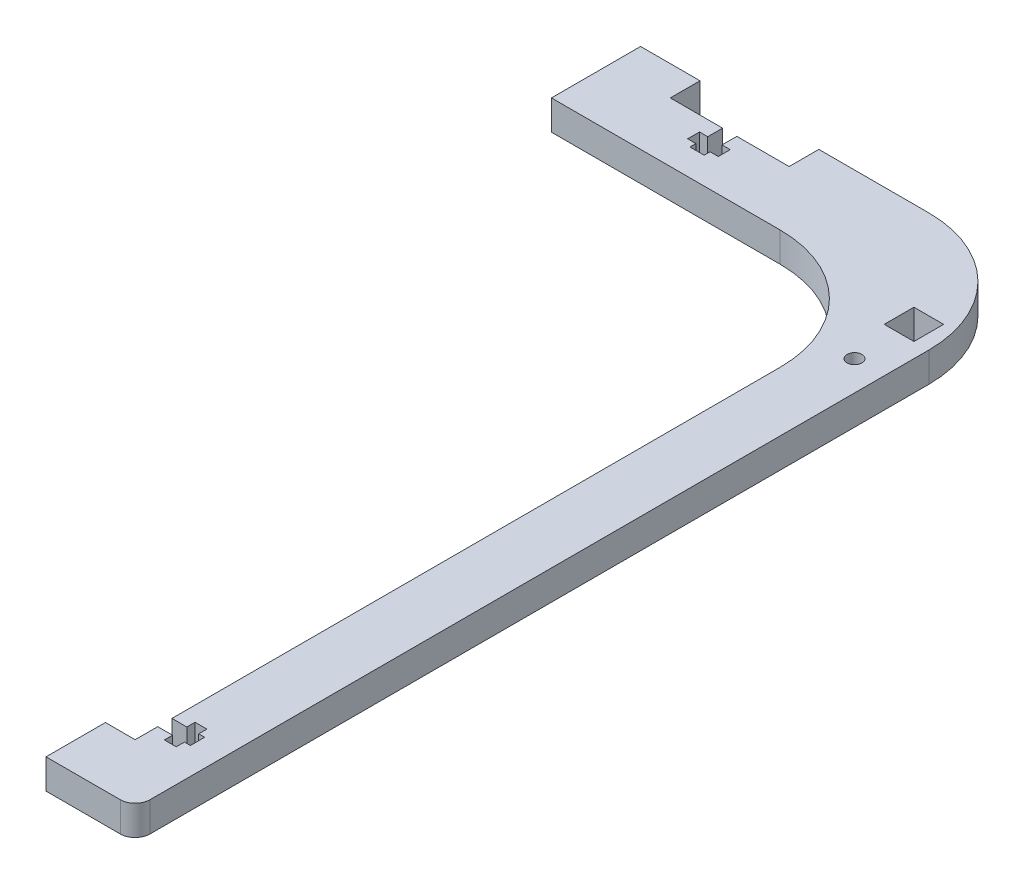
SolidWorks part; units mm, degrees
material "6061 Alloy"
ref_plane "Front Plane" through (0, 0, 0) normal (0, 0, 1) x (1, 0, 0)
ref_plane "Top Plane" through (0, 0, 0) normal (0, 1, 0) x (1, 0, 0)
ref_plane "Right Plane" through (0, 0, 0) normal (1, 0, 0) x (0, 0, -1)
sketch "Sketch1" plane through (0, 0, 0) normal (0, 1, 0) x (1, 0, 0)
  line L0 (7.8827, 29.2087) -> (-41.0123, 29.2087)
  line L1 (33.2827, 3.8087) -> (33.2827, -121.3625)
  line L2 (33.2827, -121.3625) -> (33.2827, -126.1886)
  line L3 (40.2677, -129.2364) -> (38.9977, -129.2364)
  line L4 (38.9977, -129.2364) -> (38.9977, -130.989)
  line L5 (38.9977, -130.989) -> (36.4577, -130.989)
  line L6 (36.4577, -130.989) -> (36.4577, -129.2364)
  line L7 (36.4577, -129.2364) -> (33.2827, -129.2364)
  line L8 (40.2677, -126.1886) -> (38.9977, -126.1886)
  line L9 (38.9977, -126.1886) -> (38.9977, -124.436)
  line L10 (38.9977, -124.436) -> (36.4577, -124.436)
  line L11 (36.4577, -124.436) -> (36.4577, -126.1886)
  line L12 (36.4577, -126.1886) -> (33.2827, -126.1886)
  line L13 (33.2827, -134.0625) -> (26.9327, -134.0625)
  line L14 (26.9327, -134.0625) -> (26.9327, -146.7625)
  line L15 (26.9327, -146.7625) -> (33.2827, -146.7625)
  line L16 (33.2827, -146.7625) -> (42.8077, -146.7625)
  line L17 (45.9827, -143.5875) -> (45.9827, 22.8587)
  line L18 (-41.0123, 48.2587) -> (-28.3123, 48.2587)
  line L19 (-2.9123, 48.2587) -> (20.5827, 48.2587)
  line L20 (-41.0123, 48.2587) -> (-41.0123, 29.2087)
  line L21 (-28.3123, 48.2587) -> (-28.3123, 41.9087)
  line L22 (-28.3123, 41.9087) -> (-17.1362, 41.9087)
  line L23 (-14.0884, 41.9087) -> (-2.9123, 41.9087)
  line L24 (-2.9123, 41.9087) -> (-2.9123, 48.2587)
  line L25 (-17.1362, 34.9237) -> (-17.1362, 36.1937)
  line L26 (-17.1362, 36.1937) -> (-18.8888, 36.1937)
  line L27 (-18.8888, 36.1937) -> (-18.8888, 38.7337)
  line L28 (-18.8888, 38.7337) -> (-17.1362, 38.7337)
  line L29 (-17.1362, 38.7337) -> (-17.1362, 41.9087)
  line L30 (-14.0884, 34.9237) -> (-14.0884, 36.1937)
  line L31 (-14.0884, 36.1937) -> (-12.3358, 36.1937)
  line L32 (-12.3358, 36.1937) -> (-12.3358, 38.7337)
  line L33 (-12.3358, 38.7337) -> (-14.0884, 38.7337)
  line L34 (-14.0884, 38.7337) -> (-14.0884, 41.9087)
  line L35 (39.6327, 29.2087) -> (42.8077, 29.2087)
  line L36 (42.8077, 29.2087) -> (42.8077, 22.8587)
  line L37 (42.8077, 22.8587) -> (36.4577, 22.8587)
  line L38 (36.4577, 22.8587) -> (36.4577, 29.2087)
  line L39 (36.4577, 29.2087) -> (39.6327, 29.2087)
  line L40 (-17.1362, 34.9237) -> (-14.0884, 34.9237)
  line L41 (33.2827, -129.2364) -> (33.2827, -134.0625)
  line L42 (40.2677, -126.1886) -> (40.2677, -129.2364)
  arc A0 (33.2827, 3.8087) -> (7.8827, 29.2087) centre (7.8827, 3.8087) ccw
  arc A1 (45.9827, 22.8587) -> (20.5827, 48.2587) centre (20.5827, 22.8587) ccw
  arc A2 (42.8077, -146.7625) -> (45.9827, -143.5875) centre (42.8077, -143.5875) ccw
  circle A3 centre (39.6327, 13.3337) radius 1.5875
extrude "Boss-Extrude1" add sketch "Sketch1" along normal blind 6.35
